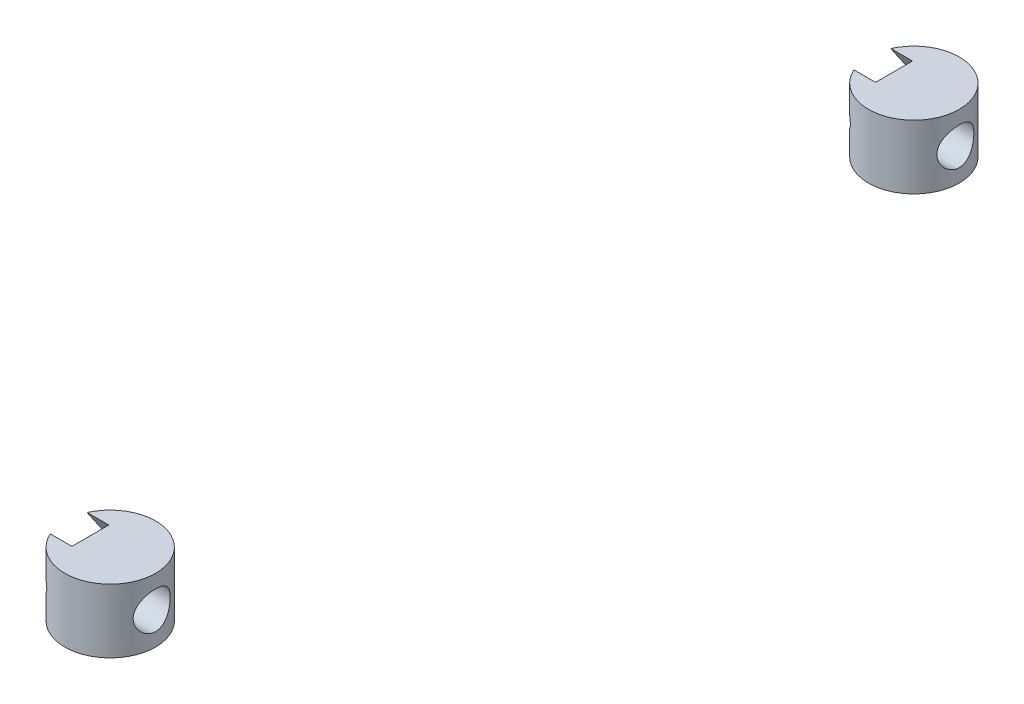
SolidWorks part; units mm, degrees
ref_plane "Front Plane" through (0, 0, 0) normal (0, 0, 1) x (1, 0, 0)
ref_plane "Top Plane" through (0, 0, 0) normal (0, 1, 0) x (1, 0, 0)
ref_plane "Right Plane" through (0, 0, 0) normal (1, 0, 0) x (0, 0, -1)
sketch "Sketch1" plane through (0, 0, 0) normal (0, 1, 0) x (1, 0, 0)
  line L2 (0, -88.9) -> (0, 88.9) construction
  circle A0 centre (0, 79.875) radius 9.025
  circle A1 centre (0, -79.875) radius 9.025
  point P0 (0, 0)
  point P1 (5.85, 82.2114)
  point P4 (0, 82.3151)
  point P10 (0, 0)
  point P11 (0, -83.4784)
  dimension "D4" = 18.05
  dimension "D2" = 177.8
extrude "Boss-Extrude1" add sketch "Sketch1" along normal blind 12.7
sketch "Sketch2" plane through (0, 0, 0) normal (1, 0, 0) x (0, 0, -1)
  line L0 (-70.85, 12.7) -> (-88.9, 12.7) construction
  line L1 (-70.85, 12.7) -> (-88.9, 12.7) construction
  line L2 (-88.9, 12.7) -> (-88.9, 0) construction
  line L3 (-88.9, 12.7) -> (-88.9, 0) construction
  line L4 (0, 12.7) -> (0, -20.396) construction
  circle A0 centre (-79.875, 6.35) radius 3.675
  circle A1 centre (79.875, 6.35) radius 3.675
  point P4 (-79.875, 12.7)
  point P7 (-88.9, 6.35)
  dimension "D1" = 7.35
extrude "Cut-Extrude1" cut sketch "Sketch2" against normal through all both and the other way through all
ref_plane "Plane1" through (-9.025, 0, 0) normal (-1, 0, 0) x (0, 0, 1)
sketch "Sketch3" plane through (-9.025, 0, 0) normal (-1, 0, 0) x (0, 0, 1)
  line L0 (70.85, 0) -> (88.9, 0) construction
  line L1 (83.5412, 0) -> (87.2073, 6.35)
  line L2 (87.2073, 6.35) -> (83.5412, 12.7)
  line L3 (83.5412, 12.7) -> (76.2088, 12.7)
  line L4 (76.2088, 12.7) -> (72.5427, 6.35)
  line L5 (72.5427, 6.35) -> (76.2088, 0)
  line L6 (76.2088, 0) -> (83.5412, 0)
  line L7 (0, 15.1212) -> (0, -17.7329) construction
  line L8 (-76.2088, 0) -> (-83.5412, 0)
  line L9 (-72.5427, 6.35) -> (-76.2088, 0)
  line L10 (-76.2088, 12.7) -> (-72.5427, 6.35)
  line L11 (-83.5412, 12.7) -> (-76.2088, 12.7)
  line L12 (-87.2073, 6.35) -> (-83.5412, 12.7)
  line L13 (-83.5412, 0) -> (-87.2073, 6.35)
  circle A0 centre (79.875, 6.35) radius 6.35 construction
  circle A1 centre (-79.875, 6.35) radius 6.35 construction
  dimension "D1" = 12.7
extrude "Cut-Extrude2" cut sketch "Sketch3" against normal blind 5.08
